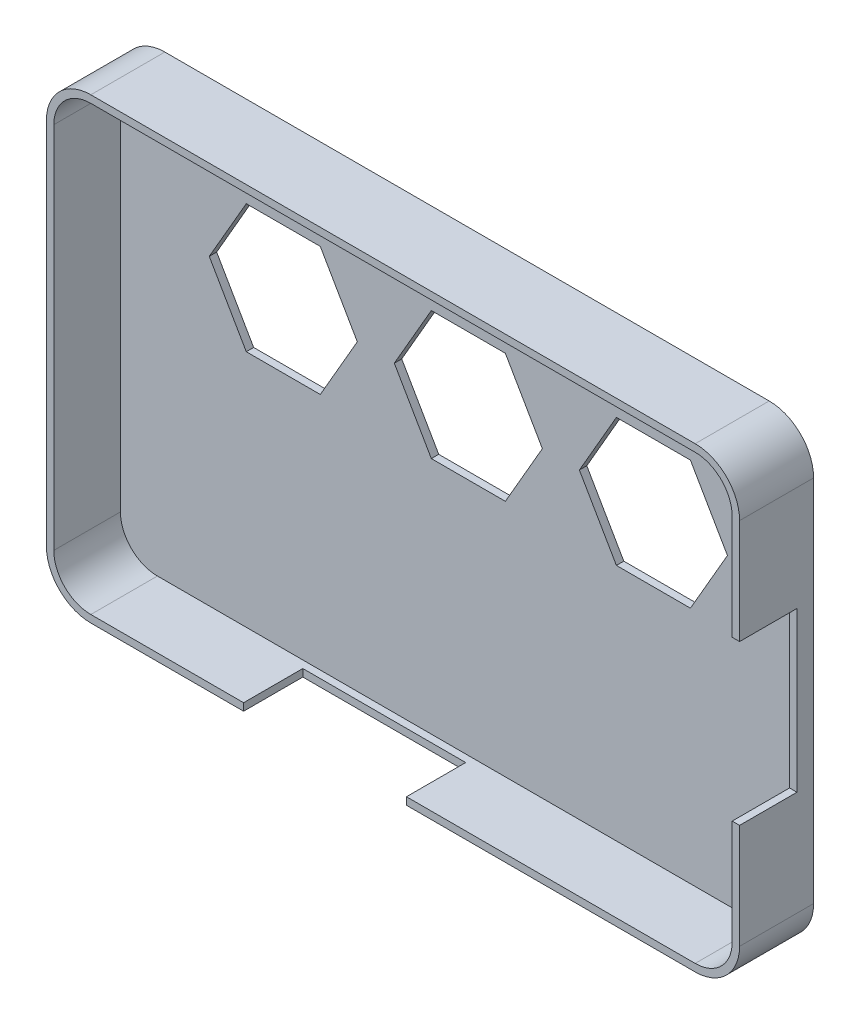
SolidWorks part; units mm, degrees
ref_plane "Ebene vorne" through (0, 0, 0) normal (1, 0, 0) x (0, 1, 0)
ref_plane "Ebene oben" through (0, 0, 0) normal (0, 0, 1) x (0, 1, 0)
ref_plane "Ebene rechts" through (0, 0, 0) normal (0, 1, 0) x (-1, 0, 0)
sketch "Skizze1" plane through (0, 0, 0) normal (0, 0, 1) x (0, 1, 0)
  line L0 (-30.9, -46.82) -> (30.9, -46.82)
  line L1 (-30.9, -46.82) -> (-30.9, 46.82)
  line L2 (-30.9, 46.82) -> (30.9, 46.82)
  line L3 (30.9, -46.82) -> (30.9, 46.82)
  line L4 (-30.9, -46.82) -> (30.9, 46.82) construction
  line L5 (-30.9, 46.82) -> (30.9, -46.82) construction
  point P0 (0, 0)
  dimension "D1" = 61.8
  dimension "D2" = 93.64
extrude "Aufsatz-Linear austragen1" add sketch "Skizze1" along normal blind 10
fillet "Verrundung1" radius 6 4 edges at (46.82, -30.9, 5) (-46.82, -30.9, 5) (-46.82, 30.9, 5) (46.82, 30.9, 5)
shell "Wandung1" thickness 1
sketch "Skizze2" plane through (46.82, 0, 0) normal (1, 0, 0) x (0, 1, 0)
  line L0 (-24.9, 10) -> (24.9, 10) construction
  line L1 (-10.75, 17.75) -> (10.75, 17.75)
  line L2 (-10.75, 17.75) -> (-10.75, 2.25)
  line L3 (-10.75, 2.25) -> (10.75, 2.25)
  line L4 (10.75, 17.75) -> (10.75, 2.25)
  line L5 (-10.75, 17.75) -> (10.75, 2.25) construction
  line L6 (-10.75, 2.25) -> (10.75, 17.75) construction
  point P0 (0, 10)
  dimension "D1" = 21.5
  dimension "D2" = 15.5
extrude "Schnitt-Linear austragen1" cut sketch "Skizze2" against normal blind 6
sketch "Skizze3" plane through (0, -30.9, 0) normal (0, -1, 0) x (1, 0, 0)
  line L0 (-40.82, 10) -> (40.82, 10) construction
  line L1 (1.82, 10) -> (-20.18, 10)
  line L2 (1.82, 10) -> (1.82, 2)
  line L3 (1.82, 2) -> (-20.18, 2)
  line L4 (-20.18, 10) -> (-20.18, 2)
  dimension "D1" = 22
  dimension "D2" = 8
  dimension "D3" = 39
extrude "Schnitt-Linear austragen2" cut sketch "Skizze3" against normal blind 6
sketch "Skizze4" plane through (0, 0, 0) normal (0, 0, -1) x (1, 0, 0)
  line L0 (-33.82, 30.9) -> (-33.82, -30.9) construction
  line L2 (-18.82, -2.3397) -> (-28.82, -2.3397)
  line L3 (-28.82, -2.3397) -> (-33.82, -11)
  line L4 (-33.82, -11) -> (-28.82, -19.6603)
  line L5 (-28.82, -19.6603) -> (-18.82, -19.6603)
  line L6 (-18.82, -19.6603) -> (-13.82, -11)
  line L7 (-13.82, -11) -> (-18.82, -2.3397)
  line L14 (-46.82, -24.9) -> (-46.82, 24.9) construction
  line L15 (-40.82, 30.9) -> (40.82, 30.9) construction
  circle A8 centre (-23.82, -11) radius 8.6603 construction
  point P3 (-33.82, 0)
  point P14 (0, 0)
  point P15 (0, 0)
  point P16 (-33.82, -14)
  dimension "D3" = 41.9
  dimension "D5" = 13
  dimension "D1" = 10
  dimension "D2" = 30.9
extrude "Schnitt-Linear austragen4" cut sketch "Skizze4" against normal blind 6
pattern_linear "Lineares Muster1" count 3 spacing 25 along (1, 0, 0) of "Schnitt-Linear austragen4"
